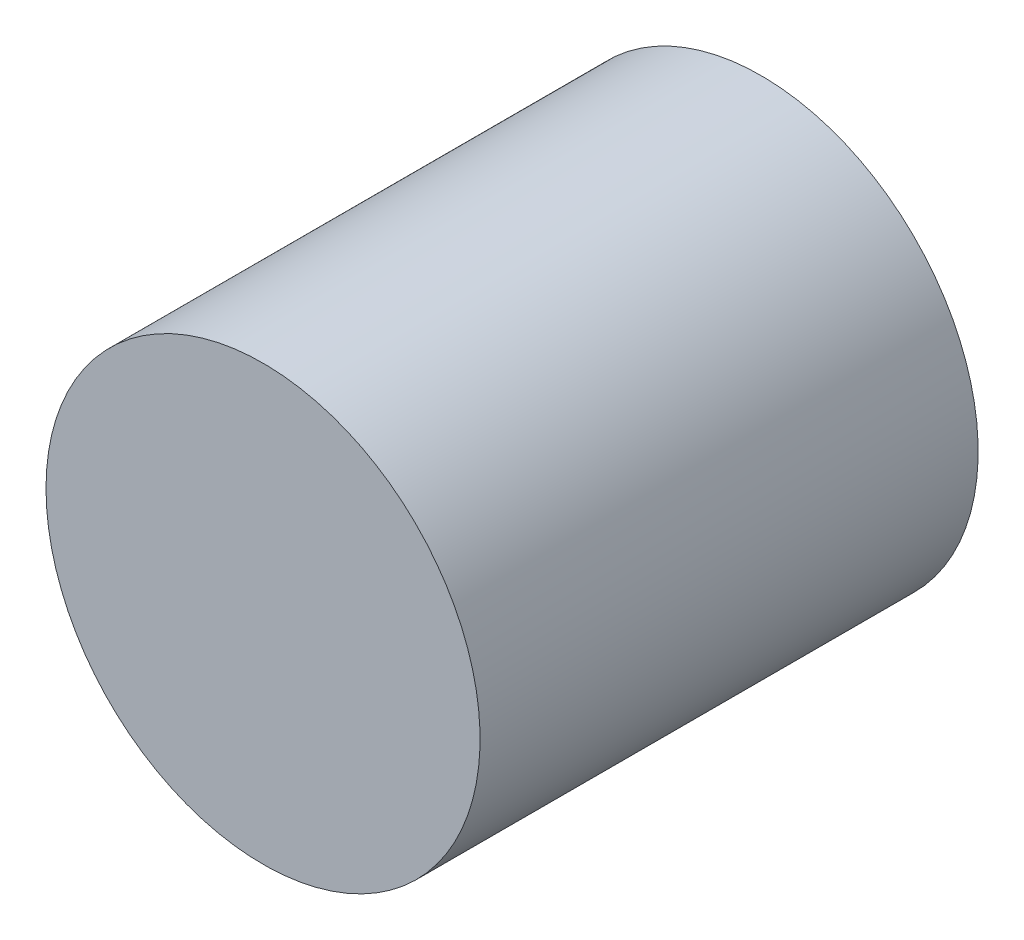
SolidWorks part; units mm, degrees
ref_plane "Front Plane" through (0, 0, 0) normal (0, 0, 1) x (1, 0, 0)
ref_plane "Top Plane" through (0, 0, 0) normal (0, 1, 0) x (1, 0, 0)
ref_plane "Right Plane" through (0, 0, 0) normal (1, 0, 0) x (0, 0, -1)
sketch "CurveSketch" plane through (0, 0, 0) normal (0, 0, 1) x (1, 0, 0)
  circle A0 centre (-3.719, 6.137) radius 5.193
  dimension "D1" = 10.386
extrude "CurveBoss" add sketch "CurveSketch" along normal blind 11.917
